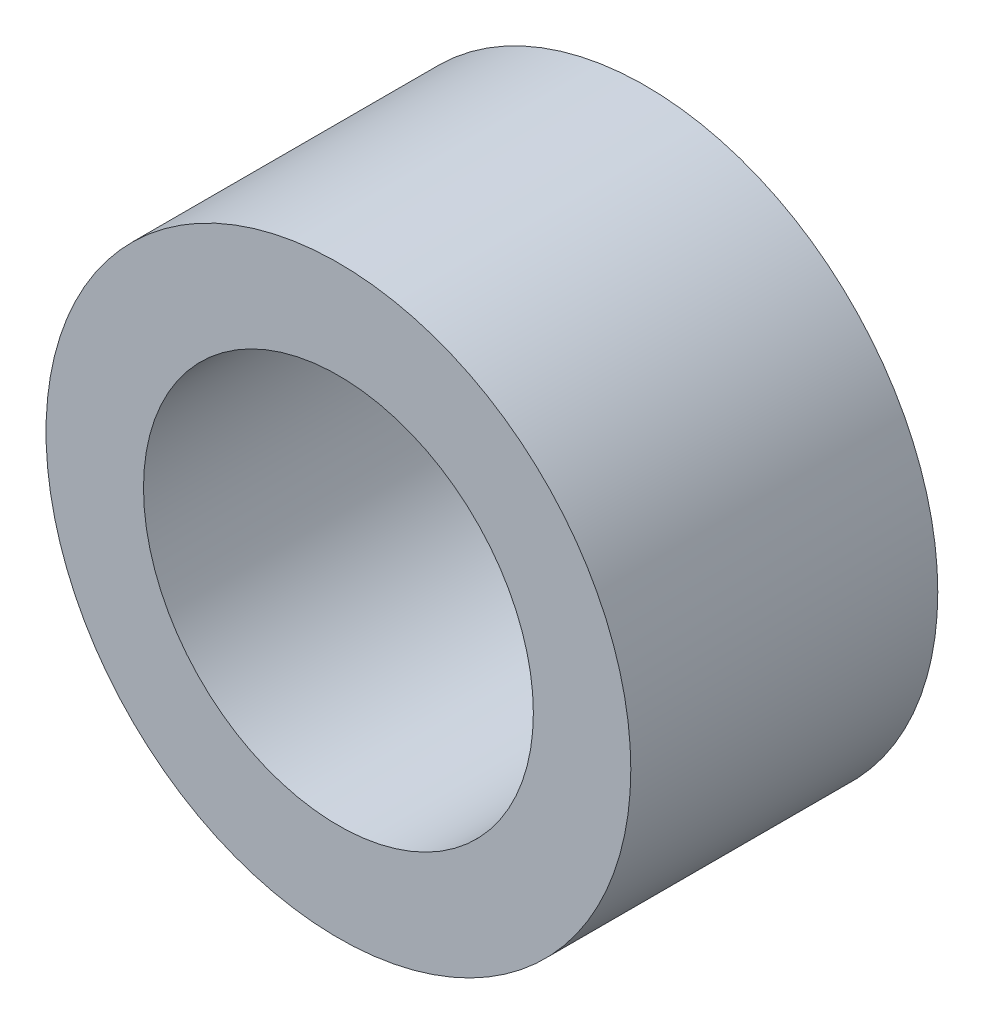
SolidWorks part; units mm, degrees
ref_plane "Plan de face" through (0, 0, 0) normal (0, 0, 1) x (1, 0, 0)
ref_plane "Plan de dessus" through (0, 0, 0) normal (0, 1, 0) x (1, 0, 0)
ref_plane "Plan de droite" through (0, 0, 0) normal (1, 0, 0) x (0, 0, -1)
sketch "Esquisse1" plane through (0, 0, 0) normal (0, 0, 1) x (1, 0, 0)
  circle A0 centre (0, 0) radius 6.35
  circle A1 centre (0, 0) radius 9.525
  dimension "D1" = 12.7
  dimension "D2" = 19.05
extrude "Boss.-Extru.1" add sketch "Esquisse1" along normal blind 10
